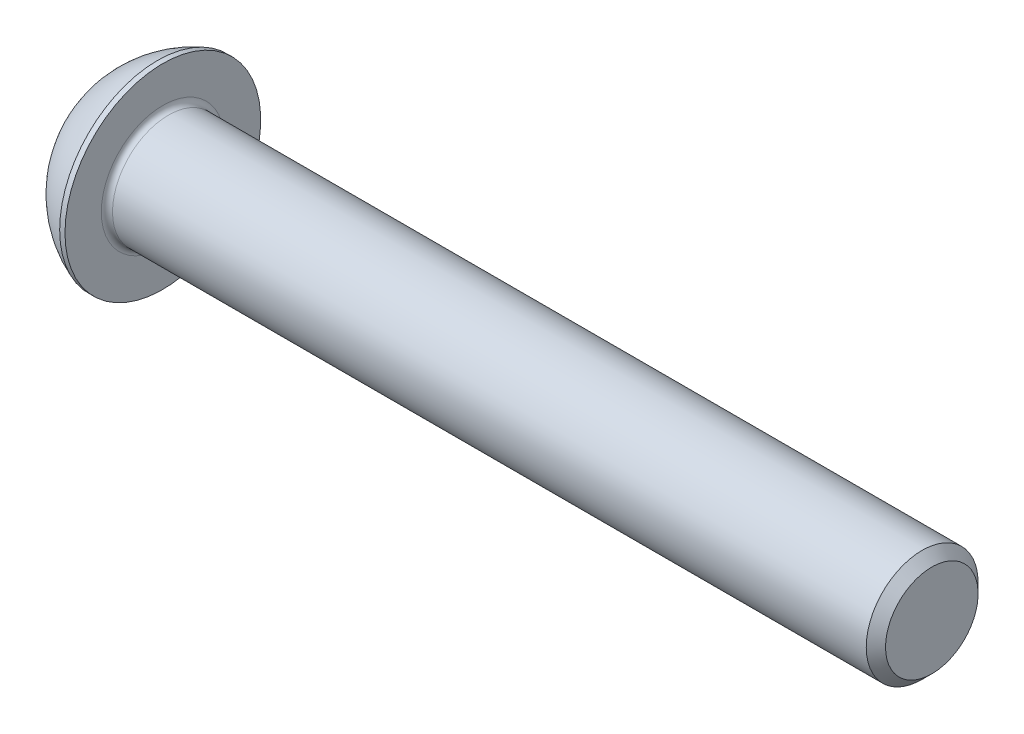
SolidWorks part; units mm, degrees
ref_plane "Plane1" through (0, 0, 0) normal (0, 0, 1) x (1, 0, 0)
ref_plane "Plane2" through (0, 0, 0) normal (0, 1, 0) x (1, 0, 0)
ref_plane "Plane3" through (0, 0, 0) normal (1, 0, 0) x (0, 0, -1)
sketch "BodySke" plane through (0, 0, 0) normal (0, 0, 1) x (1, 0, 0)
  line L0 (59.4, 0) -> (59.4, 3.3095)
  line L1 (58.7095, 4) -> (4.4, 4)
  line L2 (4.4, 4) -> (4.4, 7)
  line L3 (4.4, 7) -> (4.02, 7)
  line L4 (0, 0) -> (101.6, 0) construction
  line L5 (4.4, -7) -> (4.02, -7) construction
  line L6 (55.6768, -4) -> (4.4, -4) construction
  line L7 (59.4, 0) -> (0, 0)
  line L8 (0, 3.5) -> (0, -3.5) construction
  line L9 (0, 0) -> (0, 3.5)
  line L10 (59.4, 3.3095) -> (58.7095, 4)
  line L11 (59.4, -3.3095) -> (58.7095, -4) construction
  line L12 (5.65, 9.525) -> (5.65, -4) construction
  line L13 (4.4, 9.525) -> (4.4, -4) construction
  arc A1 (0, 3.5) -> (4.02, 7) centre (6.5809, 0) cw
  dimension "Diameter" = 8
  dimension "Length" = 55
  dimension "Head_dia" = 14
  dimension "D1" = 7
  dimension "Head_ht" = 4.4
  dimension "Head_side_ht" = 0.38
  dimension "Minor_dia" = 6.619
  dimension "Body_ch_ang" = 45
  dimension "Advance" = 1.25
  dimension "Thread_nom" = 55
revolve "BaseBody" add sketch "BodySke" angle 360 about L4
cosmetic thread "ThreadCosmetic" parameters "Thread_length"=52.5, "Thread_minor"=6.619
fillet "Fillet1" radius 0.4 1 edges at (4.4, 0, 4)
sketch "Sketch2" plane through (0, 0, 0) normal (0, 0, 1) x (1, 0, 0)
  line L0 (0, 2.5) -> (2.6, 2.5)
  line L1 (2.6, 2.5) -> (4.0434, 0)
  line L3 (4.0434, 0) -> (0, 0)
  line L4 (0, 0) -> (0, 2.5)
  line L5 (0, -2.5) -> (2.6, -2.5) construction
  line L6 (0, 0) -> (47.625, 0) construction
  dimension "D2" = 60
  dimension "PreBroach_depth" = 2.6
  dimension "PreBroach_dia" = 5
revolve "PreBroach" cut sketch "Sketch2" angle 360 about L6
sketch "Sketch3" plane through (0, 0, 0) normal (1, 0, 0) x (0, 0, -1)
  line L0 (-2.5, -1.4434) -> (-2.5, 1.4434)
  line L1 (-2.5, 1.4434) -> (0, 2.8868)
  line L2 (0, 2.8868) -> (2.5, 1.4434)
  line L3 (2.5, 1.4434) -> (2.5, -1.4434)
  line L4 (2.5, -1.4434) -> (0, -2.8868)
  line L5 (0, -2.8868) -> (-2.5, -1.4434)
  dimension "Hex_size" = 5
  dimension "D3" = 5
  dimension "D1" = 2.5
  dimension "D2" = 2.5
extrude "Hex" cut sketch "Sketch3" along normal blind 2.6
sketch "ThdSchSke" plane through (0, 0, 0) normal (0, 0, 1) x (1, 0, 0)
  line L0 (6.9, -3.3095) -> (6.4165, -4)
  line L1 (6.9, -3.3095) -> (7.3835, -4)
  line L2 (7.3835, -4) -> (7.3835, -5)
  line L3 (-3.175, 0) -> (5.1513, 0) construction
  line L5 (7.3835, -5) -> (6.4165, -5)
  line L6 (6.4165, -5) -> (6.4165, -4)
  dimension "Diameter" = 8
  dimension "Thread_minor" = 6.619
  dimension "SideAngle" = 55
  dimension "VeeAngle" = 70
  dimension "Overcut" = 10
  dimension "Start" = 6.9
revolve "ThreadSchematic" [suppressed] cut sketch "ThdSchSke" angle 360 about L3
pattern_linear "ThdSchPat" [suppressed]
equation "\"D1@BodySke\" = \"Head_dia@BodySke\" * .5"
equation "\"Thread_minor@ThreadCosmetic\" = \"Minor_dia@BodySke\""
equation "\"D1@Sketch3\" = \"Hex_size@Sketch3\" / 2"
equation "\"D2@Sketch3\" = \"D1@Sketch3\""
equation "\"D3@Sketch3\" = \"Hex_size@Sketch3\""
equation "\"Thread_length@ThreadCosmetic\" = ((sgn( (\"Length@BodySke\" - \"Advance@BodySke\" * 2.0) - \"Thread_nom@BodySke\" )-1)*( (\"Length@BodySke\" - \"Advance@BodySke\" * 2.0) - \"Thread_nom@BodySke\" ))/-2+ \"Thread_nom@BodySke\""
equation "\"Thread_minor@ThdSchSke\" = \"Minor_dia@BodySke\""
equation "\"Diameter@ThdSchSke\" = \"Diameter@BodySke\""
equation "\"Overcut@ThdSchSke\" = \"Diameter@BodySke\" * 1.25"
equation "\"Start@ThdSchSke\" = \"Head_ht@BodySke\" + \"Length@BodySke\" - \"Thread_length@ThreadCosmetic\"  '---Non-countersunk---"
equation "\"Num_threads@ThdSchPat\" = int( \"Thread_length@ThreadCosmetic\" / \"Advance@BodySke\" + 0.999 )  + 1"
equation "\"Advance@ThdSchPat\" = \"Thread_length@ThreadCosmetic\" /  (\"Num_threads@ThdSchPat\" - 1) 'relax it"
equation "\"Num_threads@ThdSchPat\" = \"Num_threads@ThdSchPat\" - sgn( \"Num_threads@ThdSchPat\" - 1) '---chamfered tips only---"
